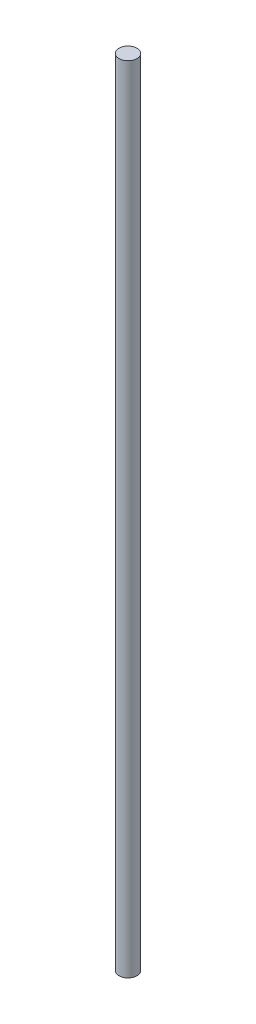
SolidWorks part; units mm, degrees
ref_plane "Front Plane" through (0, 0, 0) normal (0, 0, 1) x (1, 0, 0)
ref_plane "Top Plane" through (0, 0, 0) normal (0, 1, 0) x (1, 0, 0)
ref_plane "Right Plane" through (0, 0, 0) normal (1, 0, 0) x (0, 0, -1)
sketch "Sketch1" plane through (0, 0, 0) normal (0, 1, 0) x (1, 0, 0)
  circle A0 centre (0, 0) radius 8
  dimension "D1" = 16
extrude "Boss-Extrude1" add sketch "Sketch1" along normal blind 705
hole_wizard "M8x1.0 Tapped Hole1" positions "Sketch2" profile "Sketch4" tap size "M8x1.0" standard "ANSI Metric"
sketch "Sketch2" plane through (0, 0, 0) normal (0, -1, 0) x (-1, 0, 0)
  point P0 (0, 0)
sketch "Sketch4" plane through (0, 0, 0) normal (1, 0, 0) x (0, 0, -1)
  line L0 (0, 0) -> (0, 21.103)
  line L1 (0, 21.103) -> (3.5, 19)
  line L2 (3.5, 19) -> (3.5, 0)
  line L5 (3.5, 0) -> (0, 0)
  line L10 (0, 21.103) -> (-3.5, 19) construction
  line L11 (0, -6.35) -> (0, 107.95) construction
  dimension "Tap Drill Dia." = 7
  dimension "Tap Drill Depth" = 19
  dimension "Drill Angle" = 118
cosmetic thread "Hole Thread1"
